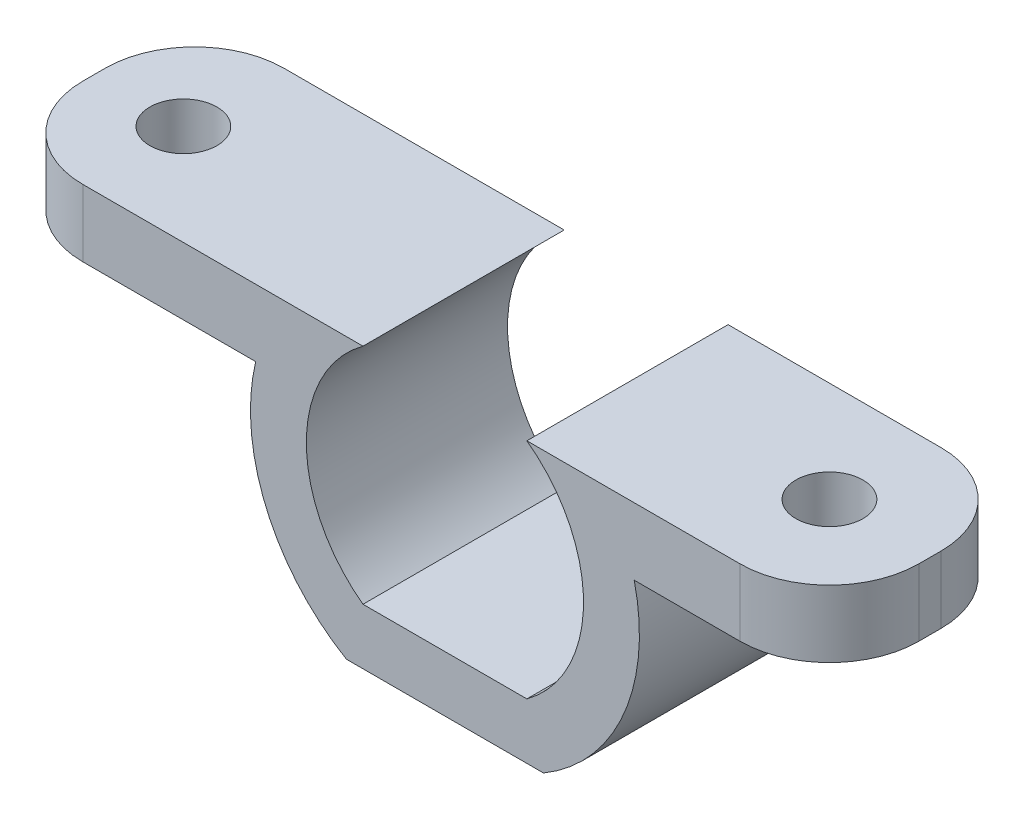
SolidWorks part; units mm, degrees
ref_plane "Front Plane" through (0, 0, 0) normal (0, 0, 1) x (1, 0, 0)
ref_plane "Top Plane" through (0, 0, 0) normal (0, 1, 0) x (1, 0, 0)
ref_plane "Right Plane" through (0, 0, 0) normal (1, 0, 0) x (0, 0, -1)
sketch "Sketch1" plane through (0, 0, 0) normal (0, 0, 1) x (1, 0, 0)
  line L0 (5.8686, 2) -> (17.2, 2)
  line L1 (-3.6661, 5) -> (3.6661, 5)
  line L2 (-3.6661, -5) -> (3.6661, -5)
  line L10 (-4.4091, -7.5) -> (4.4091, -7.5)
  line L13 (-20.2, 5) -> (17.2, 5)
  line L14 (-20.2, 5) -> (-20.2, 2)
  line L15 (-20.2, 2) -> (-5.8686, 2)
  line L16 (17.2, 5) -> (17.2, 2)
  arc A0 (3.6661, -5) -> (3.6661, 5) centre (0, 0) ccw
  arc A1 (-7.1197, 5) -> (-4.4091, -7.5) centre (0, 0) ccw
  arc A2 (4.4091, -7.5) -> (7.1197, 5) centre (0, 0) ccw
  arc A3 (-3.6661, 5) -> (-3.6661, -5) centre (0, 0) ccw
  point P14 (-8.7, 0)
  dimension "D2" = 10
  dimension "D3" = 2.5
  dimension "D6" = 11.5
  dimension "D1" = 6.2
  dimension "D7" = 17.2
  dimension "D4" = 3
  dimension "D5" = 2.5
extrude "Boss-Extrude1" add sketch "Sketch1" along normal blind 9
sketch "Sketch2" plane through (0, 2, 0) normal (0, -1, 0) x (1, 0, 0)
  line L0 (-14.2975, 4.5) -> (11.5824, 4.5) construction
  line L1 (-20.2, 9) -> (-20.2, 0) construction
  line L2 (17.2, 9) -> (17.2, 0) construction
  circle A0 centre (-16.2, 4.5) radius 1.5
  circle A1 centre (12.7, 4.5) radius 1.5
  point P1 (-20.2, 4.5)
  point P9 (-14.7, 4.5)
  point P10 (11.2, 4.5)
  point P12 (14.2, 4.5)
  dimension "D1" = 3
  dimension "D2" = 3
  dimension "D3" = 28.9
  dimension "D4" = 3
extrude "Cut-Extrude1" cut sketch "Sketch2" against normal blind 10
fillet "Fillet1" radius 4 4 edges at (17.2, 3.5, 0) (17.2, 3.5, 9) (-20.2, 3.5, 0) (-20.2, 3.5, 9)
